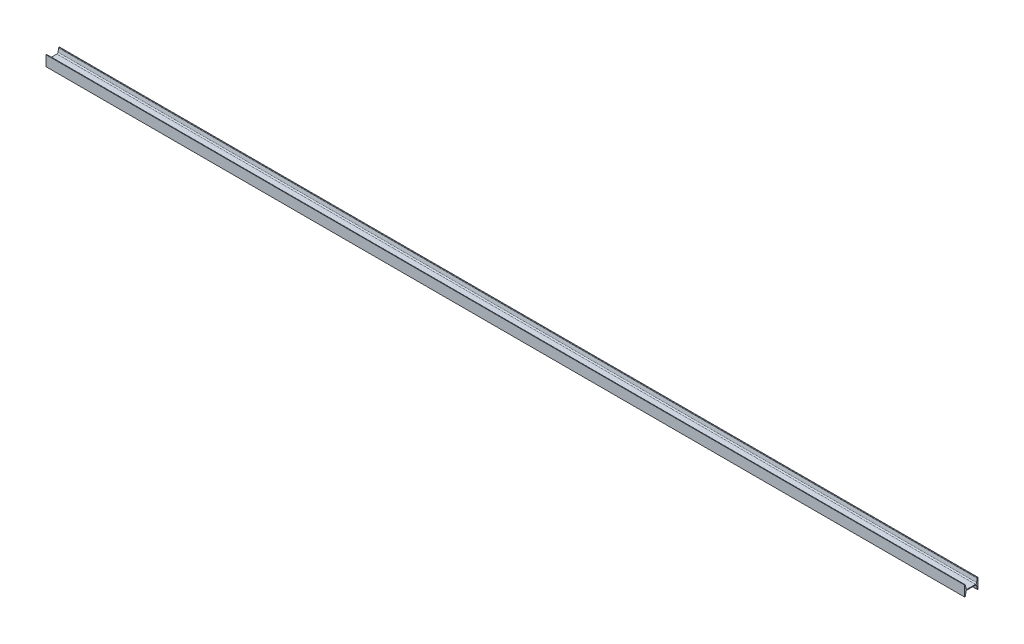
SolidWorks part; units mm, degrees
ref_plane "Front Plane" through (0, 0, 0) normal (0, 0, 1) x (1, 0, 0)
ref_plane "Top Plane" through (0, 0, 0) normal (0, 1, 0) x (1, 0, 0)
ref_plane "Right Plane" through (0, 0, 0) normal (1, 0, 0) x (0, 0, -1)
sketch "Sketch1" plane through (0, 0, 0) normal (0, 0, 1) x (1, 0, 0)
  line L0 (-2142.734, 107.1367) -> (3076.966, 107.1367)
  dimension "D1" = 5219.7
other "S section 3 X 5.7(1)"
ref_plane "Plane1" through (-2142.734, 107.1367, 0) normal (1, 0, 0) x (0, 1, 0)
sketch "Sketch11" plane through (-2142.734, 107.1367, 0) normal (1, 0, 0) x (0, 1, 0)
  line L0 (-29.591, -38.1) -> (-29.591, -35.9338)
  line L1 (-27.4686, -33.4284) -> (-7.8895, -30.165)
  line L2 (-2.159, -23.4003) -> (-2.159, 23.4003)
  line L3 (-7.8895, 30.165) -> (-27.4686, 33.4284)
  line L4 (-29.591, 35.9338) -> (-29.591, 38.1)
  line L5 (-29.591, 38.1) -> (29.591, 38.1)
  line L6 (29.591, 38.1) -> (29.591, 35.9338)
  line L7 (27.4686, 33.4284) -> (7.8895, 30.165)
  line L8 (2.159, 23.4003) -> (2.159, -23.4003)
  line L9 (7.8895, -30.165) -> (27.4686, -33.4284)
  line L10 (29.591, -35.9338) -> (29.591, -38.1)
  line L11 (29.591, -38.1) -> (-29.591, -38.1)
  line L15 (-2.159, 0) -> (2.159, 0) construction
  arc A0 (-7.8895, -30.165) -> (-2.159, -23.4003) centre (-9.017, -23.4003) ccw
  arc A1 (-2.159, 23.4003) -> (-7.8895, 30.165) centre (-9.017, 23.4003) ccw
  arc A2 (7.8895, 30.165) -> (2.159, 23.4003) centre (9.017, 23.4003) ccw
  arc A3 (2.159, -23.4003) -> (7.8895, -30.165) centre (9.017, -23.4003) ccw
  arc A4 (-27.4686, 33.4284) -> (-29.591, 35.9338) centre (-27.051, 35.9338) cw
  arc A5 (27.4686, 33.4284) -> (29.591, 35.9338) centre (27.051, 35.9338) ccw
  arc A6 (-29.591, -35.9338) -> (-27.4686, -33.4284) centre (-27.051, -35.9338) cw
  arc A7 (29.591, -35.9338) -> (27.4686, -33.4284) centre (27.051, -35.9338) ccw
  point P1 (0, 38.1)
  point P8 (0, -38.1)
  point P21 (0, 0)
  point P34 (0, 0)
  dimension "D7" = 9.463
  dimension "RI" = 6.858
  dimension "D2" = 2.54
  dimension "BF" = 59.182
  dimension "DEPTH" = 76.2
  dimension "TW" = 4.318
  dimension "D1" = 46.8006
